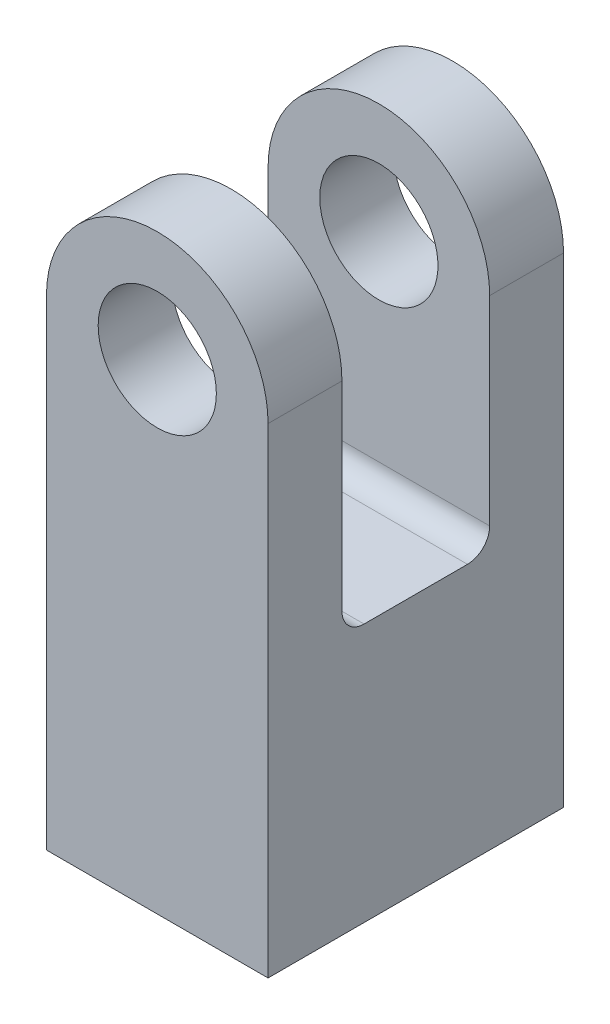
SolidWorks part; units mm, degrees
material "Простая углеродистая сталь"
ref_plane "Front" through (0, 0, 0) normal (0, 0, 1) x (1, 0, 0)
ref_plane "Top" through (0, 0, 0) normal (0, 1, 0) x (1, 0, 0)
ref_plane "Right" through (0, 0, 0) normal (1, 0, 0) x (0, 0, -1)
sketch "Эскиз1" plane through (0, 0, 0) normal (0, 0, 1) x (1, 0, 0)
  line L0 (0, 0) -> (30, 0)
  line L1 (30, 0) -> (30, 65)
  line L2 (0, 65) -> (0, 0)
  arc A0 (30, 65) -> (0, 65) centre (15, 65) ccw
  circle A1 centre (15, 65) radius 8
  dimension "D1" = 16
  dimension "D2" = 30
  dimension "D3" = 65
extrude "Бобышка-Вытянуть1" add sketch "Эскиз1" along normal blind 40
sketch "Эскиз2" plane through (0, 0, 0) normal (0, 0, 1) x (1, 0, 0)
  line L0 (30, 0) -> (30, 65) construction
  line L1 (0, 35) -> (30, 35)
  line L2 (0, 35) -> (0, 80)
  line L3 (0, 80) -> (30, 80)
  line L4 (30, 35) -> (30, 80)
  line L5 (0, 65) -> (0, 0) construction
  arc A0 (30, 65) -> (0, 65) centre (15, 65) ccw construction
  circle A1 centre (15, 65) radius 8 construction
  dimension "D1" = 30
extrude "Вырез-Вытянуть1" cut sketch "Эскиз2" against normal mid plane 20 from offset 20
fillet "Скругление1" radius 3 2 edges at (15, 35, 30) (15, 35, 10)
